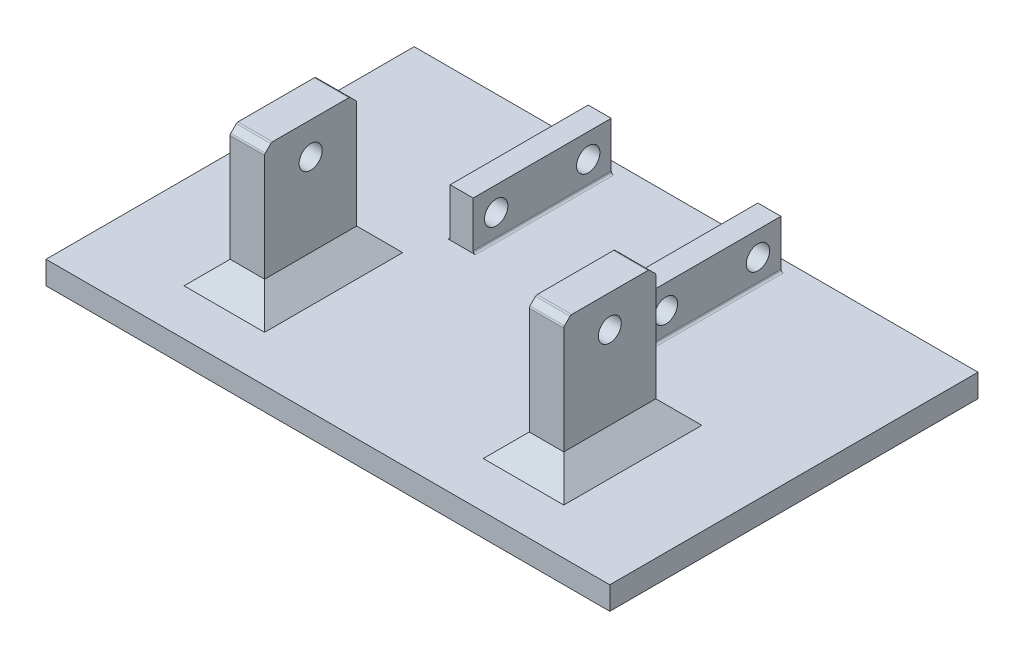
SolidWorks part; units mm, degrees
ref_plane "Front Plane" through (0, 0, 0) normal (0, 0, 1) x (1, 0, 0)
ref_plane "Top Plane" through (0, 0, 0) normal (0, 1, 0) x (1, 0, 0)
ref_plane "Right Plane" through (0, 0, 0) normal (1, 0, 0) x (0, 0, -1)
sketch "Sketch1" plane through (0, 0, 0) normal (0, 1, 0) x (1, 0, 0)
  line L1 (0, 0) -> (245, 0)
  line L2 (0, 0) -> (0, 160)
  line L3 (0, 160) -> (245, 160)
  line L4 (245, 0) -> (245, 160)
  dimension "D1" = 245
  dimension "D2" = 160
extrude "Boss-Extrude1" add sketch "Sketch1" along normal blind 10
sketch "Sketch2" plane through (0, 10, 0) normal (0, 1, 0) x (1, 0, 0)
  line L0 (0, 100) -> (245, 100) construction
  line L1 (0, 160) -> (0, 0) construction
  line L2 (245, 0) -> (245, 160) construction
  line L3 (245, 160) -> (0, 160) construction
  line L4 (0, 50) -> (245, 50) construction
  line L5 (0, 0) -> (245, 0) construction
  line L7 (50, 70) -> (65, 70)
  line L8 (50, 70) -> (50, 30)
  line L9 (50, 30) -> (65, 30)
  line L10 (65, 70) -> (65, 30)
  line L11 (50, 70) -> (65, 30) construction
  line L12 (50, 30) -> (65, 70) construction
  line L13 (180, 70) -> (195, 70)
  line L14 (180, 70) -> (180, 30)
  line L15 (180, 30) -> (195, 30)
  line L16 (195, 70) -> (195, 30)
  line L17 (180, 70) -> (195, 30) construction
  line L18 (180, 30) -> (195, 70) construction
  point P12 (57.5, 50)
  point P17 (187.5, 50)
  dimension "D5" = 40
  dimension "D6" = 40
  dimension "D1" = 60
  dimension "D2" = 50
  dimension "D3" = 15
  dimension "D4" = 15
  dimension "D7" = 145
  dimension "D8" = 50
extrude "Boss-Extrude3" add sketch "Sketch2" along normal blind 60
sketch "Sketch3" plane through (195, 0, 0) normal (1, 0, 0) x (0, 0, -1)
  line L0 (50, 70) -> (50, 10) construction
  line L1 (30, 70) -> (70, 70) construction
  line L2 (30, 10) -> (70, 10) construction
  circle A0 centre (50, 56) radius 5
  dimension "D1" = 10
  dimension "D2" = 14
extrude "Cut-Extrude1" cut sketch "Sketch3" against normal blind 146 contours A0
chamfer "Chamfer1" distance 10 angle 45 8 edges at (187.5, 10, -70) (180, 10, -50) (187.5, 10, -30) (195, 10, -50) (57.5, 10, -70) (50, 10, -50) (57.5, 10, -30) (65, 10, -50)
chamfer "Chamfer2" distance 3 angle 45 4 edges at (57.5, 70, -30) (57.5, 70, -70) (187.5, 70, -70) (187.5, 70, -30)
fillet "Fillet1" radius 1 8 edges at (57.5, 67, -70) (57.5, 70, -67) (57.5, 67, -30) (57.5, 70, -33) (187.5, 67, -30) (187.5, 70, -33) (187.5, 67, -70) (187.5, 70, -67)
sketch "Sketch4" plane through (0, 10, 0) normal (0, 1, 0) x (1, 0, 0)
  line L0 (0, 90) -> (245, 90) construction
  line L1 (0, 160) -> (0, 0) construction
  line L2 (245, 0) -> (245, 160) construction
  line L3 (245, 160) -> (0, 160) construction
  line L4 (106.375, 0) -> (106.375, 160) construction
  line L5 (0, 0) -> (245, 0) construction
  line L6 (138.625, 160) -> (138.625, 0) construction
  line L7 (0, 125) -> (245, 125) construction
  line L9 (80.625, 155) -> (90.625, 155)
  line L10 (80.625, 155) -> (80.625, 95)
  line L11 (80.625, 95) -> (90.625, 95)
  line L12 (90.625, 155) -> (90.625, 95)
  line L13 (80.625, 155) -> (90.625, 95) construction
  line L14 (80.625, 95) -> (90.625, 155) construction
  line L15 (154.375, 155) -> (164.375, 155)
  line L16 (154.375, 155) -> (154.375, 95)
  line L17 (154.375, 95) -> (164.375, 95)
  line L18 (164.375, 155) -> (164.375, 95)
  line L19 (154.375, 155) -> (164.375, 95) construction
  line L20 (154.375, 95) -> (164.375, 155) construction
  point P16 (85.625, 125)
  point P21 (159.375, 125)
  dimension "D1" = 70
  dimension "D3" = 106.375
  dimension "D4" = 83.75
  dimension "D5" = 35
extrude "Boss-Extrude4" add sketch "Sketch4" along normal blind 20.85
sketch "Sketch7" plane through (164.375, 0, 0) normal (1, 0, 0) x (0, 0, -1)
  line L0 (95, 20.425) -> (155, 20.425) construction
  line L1 (95, 30.85) -> (95, 10) construction
  line L2 (155, 30.85) -> (155, 10) construction
  circle A0 centre (105, 20.425) radius 5.075
  circle A1 centre (145, 20.425) radius 5.075
  dimension "D1" = 10.15
  dimension "D2" = 10.15
  dimension "D3" = 40
  dimension "D4" = 10
extrude "Cut-Extrude2" cut sketch "Sketch7" against normal blind 86
fillet "Fillet2" radius 1 4 edges at (80.625, 10, -125) (90.625, 10, -125) (154.375, 10, -125) (164.375, 10, -125)
